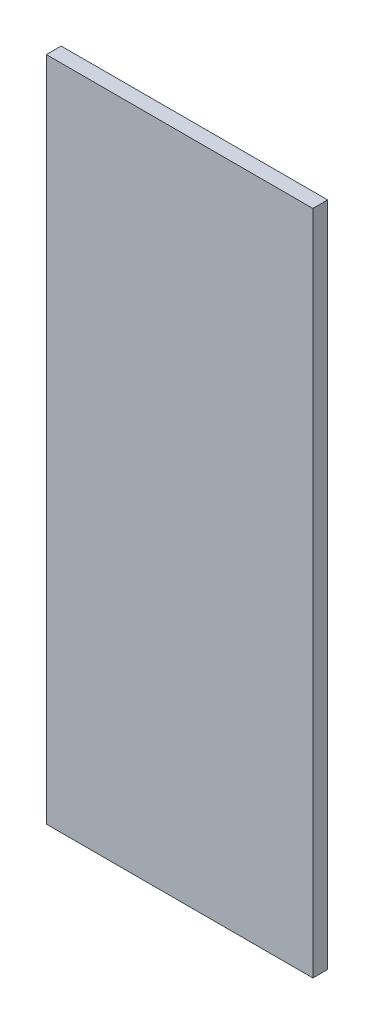
SolidWorks part; units mm, degrees
ref_plane "Front Plane" through (0, 0, 0) normal (0, 0, 1) x (1, 0, 0)
ref_plane "Top Plane" through (0, 0, 0) normal (0, 1, 0) x (1, 0, 0)
ref_plane "Right Plane" through (0, 0, 0) normal (1, 0, 0) x (0, 0, -1)
sketch "Sketch1" plane through (0, 0, 0) normal (0, 0, 1) x (1, 0, 0)
  line L1 (-57.15, 142.8745) -> (57.15, 142.8745)
  line L2 (-57.15, 142.8745) -> (-57.15, -142.8745)
  line L3 (-57.15, -142.8745) -> (57.15, -142.8745)
  line L4 (57.15, 142.8745) -> (57.15, -142.8745)
  line L5 (-57.15, 142.8745) -> (57.15, -142.8745) construction
  line L6 (-57.15, -142.8745) -> (57.15, 142.8745) construction
  point P0 (0, 0)
  dimension "D1" = 114.3
  dimension "D2" = 285.749
extrude "Boss-Extrude1" add sketch "Sketch1" along normal blind 6.35
